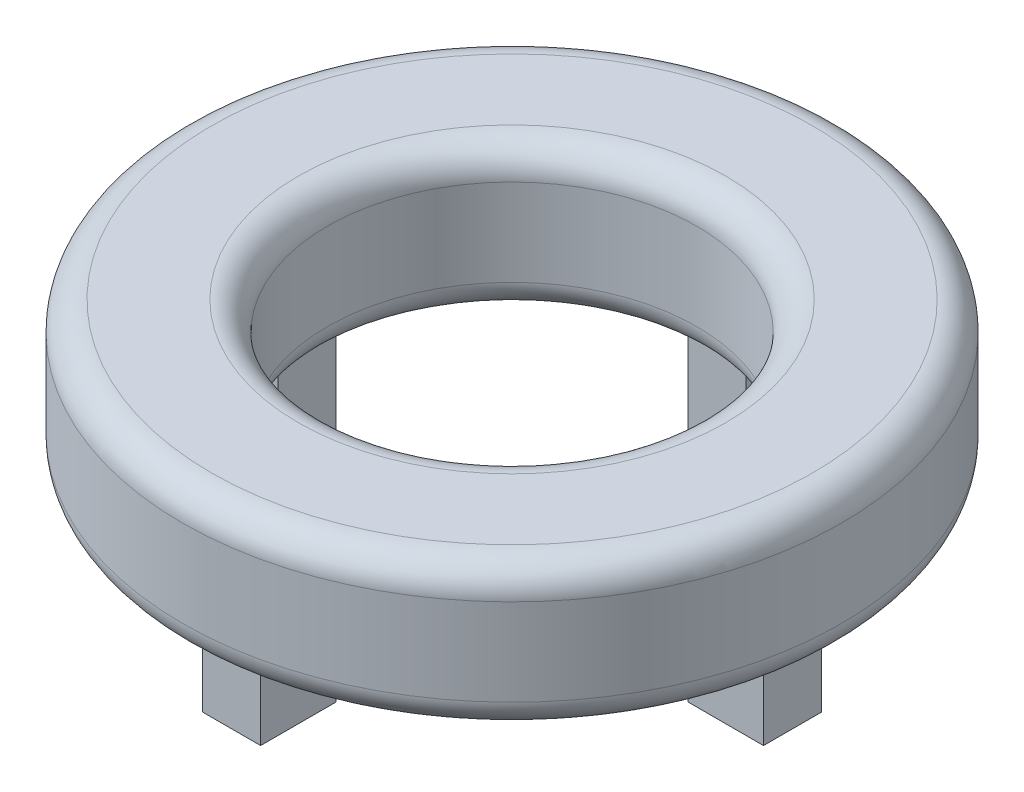
SolidWorks part; units mm, degrees
material "Серое литое железо"
ref_plane "Спереди" through (0, 0, 0) normal (0, 0, 1) x (1, 0, 0)
ref_plane "Сверху" through (0, 0, 0) normal (0, 1, 0) x (1, 0, 0)
ref_plane "Справа" through (0, 0, 0) normal (1, 0, 0) x (0, 0, -1)
sketch "Эскиз1" plane through (0, 0, 16.5) normal (0, 1, 0) x (1, 0, 0)
  circle A1 centre (0, 16.5) radius 56.8859
extrude "Вытянуть-Тонкостенный1" add sketch "Эскиз1" along normal blind 25 thin thin type one direction reverse wall 25
fillet "Скругление1" radius 5 4 edges at (31.8859, 0, 0) (0, 0, 56.8859) (31.8859, 25, 0) (0, 25, 56.8859)
sketch "Эскиз3" plane through (0, 0, 0) normal (1, 0, 0) x (0, 0, -1)
  line L0 (0, 0) -> (0, -17.0396) construction
sketch "Эскиз2" plane through (0, 0, 0) normal (0, -1, 0) x (1, 0, 0)
  line L1 (-48.4, 5) -> (-35.4, 5)
  line L2 (-48.4, 5) -> (-48.4, -5)
  line L3 (-48.4, -5) -> (-35.4, -5)
  line L4 (-35.4, 5) -> (-35.4, -5)
  line L5 (-48.4, 5) -> (-35.4, -5) construction
  line L6 (-48.4, -5) -> (-35.4, 5) construction
  circle A0 centre (-41.9, 0) radius 2.25
  point P0 (-41.9, 0)
extrude "Бобышка-Вытянуть1" add sketch "Эскиз2" along normal blind 15
pattern_circular "Круговой массив1" count 4 over 360 about axis through (0, 0, 0) along (0, 1, 0) of "Бобышка-Вытянуть1"
